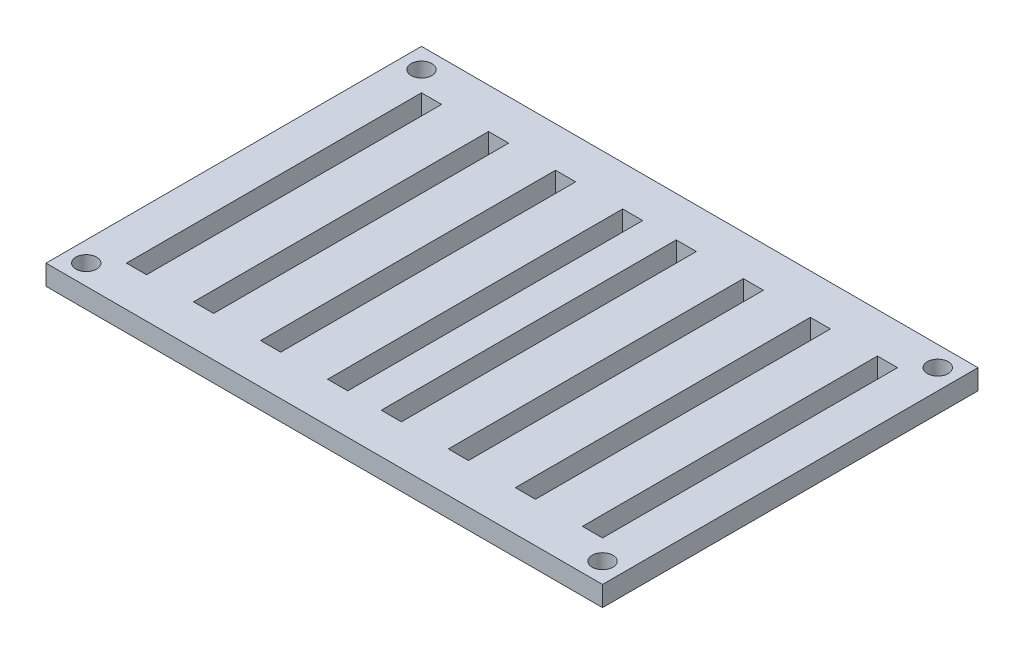
SolidWorks part; units mm, degrees
ref_plane "正面" through (0, 0, 0) normal (0, 0, 1) x (1, 0, 0)
ref_plane "平面" through (0, 0, 0) normal (0, 1, 0) x (1, 0, 0)
ref_plane "右側面" through (0, 0, 0) normal (1, 0, 0) x (0, 0, -1)
sketch "ｽｹｯﾁ1" plane through (0, 0, 0) normal (0, 1, 0) x (1, 0, 0)
  line L0 (-41.5, 28) -> (41.5, 28)
  line L1 (-38.5, 25) -> (38.5, 25) construction
  line L2 (-38.5, 25) -> (-38.5, -25) construction
  line L3 (-38.5, -25) -> (38.5, -25) construction
  line L4 (38.5, 25) -> (38.5, -25) construction
  line L5 (-38.5, 25) -> (38.5, -25) construction
  line L6 (-38.5, -25) -> (38.5, 25) construction
  line L7 (41.5, 28) -> (41.5, -28)
  line L8 (-41.5, -28) -> (41.5, -28)
  line L9 (-41.5, 28) -> (-41.5, -28)
  circle A0 centre (-38.5, 25) radius 1.55
  circle A1 centre (38.5, 25) radius 1.55
  circle A2 centre (38.5, -25) radius 1.55
  circle A3 centre (-38.5, -25) radius 1.55
  point P0 (0, 0)
  dimension "D3" = 3.1
  dimension "D1" = 77
  dimension "D2" = 50
  dimension "D4" = 3
extrude "ﾎﾞｽ - 押し出し1" add sketch "ｽｹｯﾁ1" along normal blind 3
sketch "ｽｹｯﾁ2" plane through (0, 3, 0) normal (0, 1, 0) x (1, 0, 0)
  text T0 "<b>Circuit board</b>" font "Century Gothic" height 8
extrude "ﾎﾞｽ - 押し出し2" [suppressed] add sketch "ｽｹｯﾁ2" along normal blind 1
sketch "ｽｹｯﾁ3" plane through (0, 3, 0) normal (0, 1, 0) x (1, 0, 0)
  line L0 (-41.5, 28) -> (-41.5, -28) construction
  line L1 (-35.5, 22) -> (-32.5, 22)
  line L2 (-35.5, 22) -> (-35.5, -22)
  line L3 (-35.5, -22) -> (-32.5, -22)
  line L4 (-32.5, 22) -> (-32.5, -22)
  line L5 (41.5, 28) -> (-41.5, 28) construction
  line L6 (-41.5, -28) -> (41.5, -28) construction
  line L7 (-22.5, 22) -> (-22.5, -22)
  line L8 (-25.5, 22) -> (-22.5, 22)
  line L9 (-25.5, 22) -> (-25.5, -22)
  line L10 (-25.5, -22) -> (-22.5, -22)
  line L11 (-12.5, 22) -> (-12.5, -22)
  line L12 (-15.5, 22) -> (-12.5, 22)
  line L13 (-15.5, 22) -> (-15.5, -22)
  line L14 (-15.5, -22) -> (-12.5, -22)
  line L15 (-2.5, 22) -> (-2.5, -22)
  line L16 (-5.5, 22) -> (-2.5, 22)
  line L17 (-5.5, 22) -> (-5.5, -22)
  line L18 (-5.5, -22) -> (-2.5, -22)
  line L19 (0, 28) -> (0, -28) construction
  line L20 (5.5, -22) -> (2.5, -22)
  line L21 (5.5, 22) -> (5.5, -22)
  line L22 (5.5, 22) -> (2.5, 22)
  line L23 (2.5, 22) -> (2.5, -22)
  line L24 (15.5, -22) -> (12.5, -22)
  line L25 (15.5, 22) -> (15.5, -22)
  line L26 (15.5, 22) -> (12.5, 22)
  line L27 (12.5, 22) -> (12.5, -22)
  line L28 (25.5, -22) -> (22.5, -22)
  line L29 (25.5, 22) -> (25.5, -22)
  line L30 (25.5, 22) -> (22.5, 22)
  line L31 (22.5, 22) -> (22.5, -22)
  line L32 (32.5, 22) -> (32.5, -22)
  line L33 (35.5, -22) -> (32.5, -22)
  line L34 (35.5, 22) -> (35.5, -22)
  line L35 (35.5, 22) -> (32.5, 22)
  dimension "D1" = 3
  dimension "D2" = 6
  dimension "D3" = 6
  dimension "D4" = 6
  dimension "D6" = 10
  dimension "D5" = 4
extrude "ｶｯﾄ - 押し出し1" cut sketch "ｽｹｯﾁ3" against normal through all
